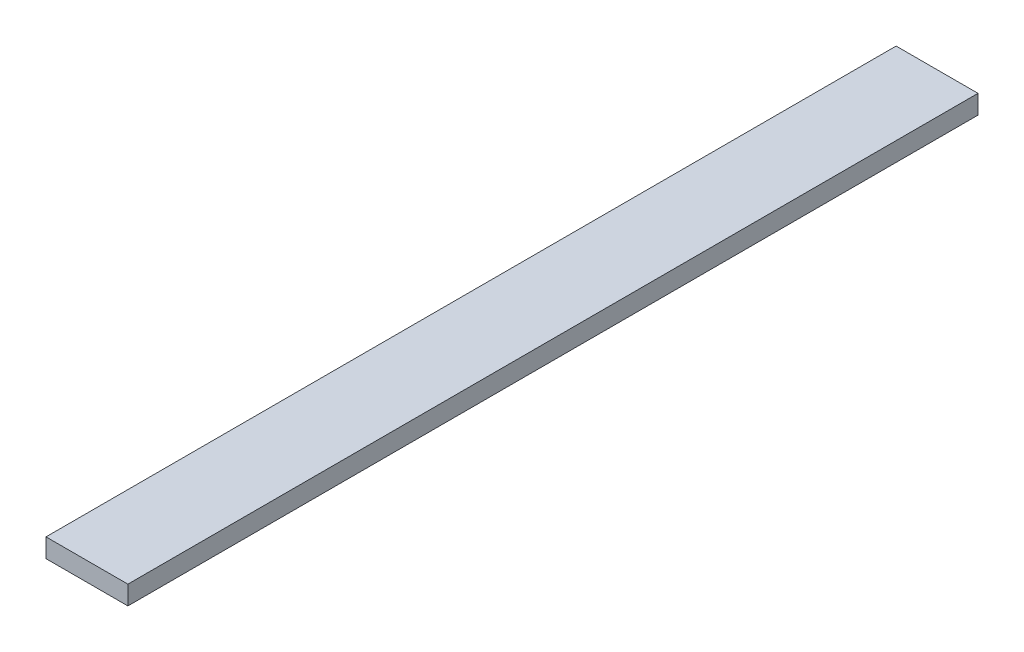
SolidWorks part; units mm, degrees
ref_plane "Front Plane" through (0, 0, 0) normal (0, 0, 1) x (1, 0, 0)
ref_plane "Top Plane" through (0, 0, 0) normal (0, 1, 0) x (1, 0, 0)
ref_plane "Right Plane" through (0, 0, 0) normal (1, 0, 0) x (0, 0, -1)
sketch "Sketch1" plane through (0, 0, 0) normal (0, 0, 1) x (1, 0, 0)
  line L1 (0, 0) -> (41.275, 0)
  line L2 (0, 0) -> (0, 9.525)
  line L3 (0, 9.525) -> (41.275, 9.525)
  line L4 (41.275, 0) -> (41.275, 9.525)
  dimension "D1" = 9.525
  dimension "D2" = 41.275
extrude "Boss-Extrude1" add sketch "Sketch1" along normal blind 428.498
